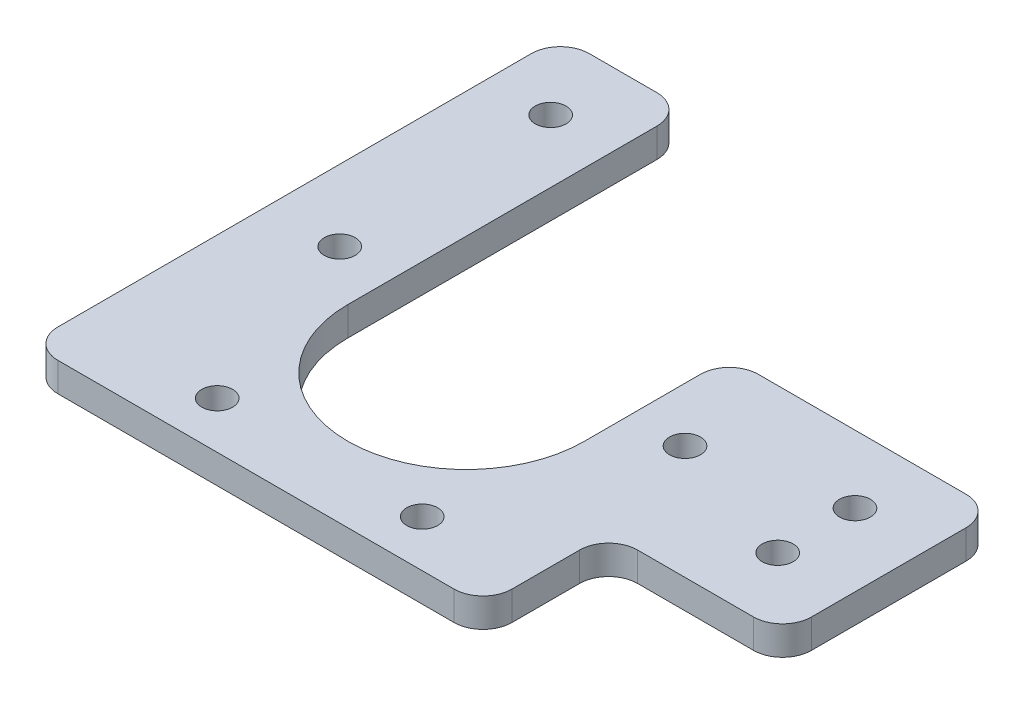
SolidWorks part; units mm, degrees
material "Thornel Mat VMA"
ref_plane "前视基准面" through (0, 0, 0) normal (0, 0, 1) x (1, 0, 0)
ref_plane "上视基准面" through (0, 0, 0) normal (0, 1, 0) x (1, 0, 0)
ref_plane "右视基准面" through (0, 0, 0) normal (1, 0, 0) x (0, 0, -1)
other "Configuration Table"
sketch "草图1" plane through (0, 0, 0) normal (0, 1, 0) x (1, 0, 0)
  line L0 (-20, -57.5) -> (-20, 57.5) construction
  line L1 (-35, -72.5) -> (35, -72.5) construction
  line L2 (-35, -72.5) -> (-35, 72.5) construction
  line L3 (-35, 72.5) -> (35, 72.5) construction
  line L4 (35, -72.5) -> (35, 72.5) construction
  line L5 (-35, -72.5) -> (35, 72.5) construction
  line L6 (-35, 72.5) -> (35, -72.5) construction
  line L7 (-20, 57.5) -> (20, 57.5) construction
  line L8 (20, -57.5) -> (20, 57.5) construction
  line L9 (-20, -57.5) -> (20, -57.5) construction
  line L10 (-7, 72.5) -> (-7, 57.5) construction
  line L11 (-17, 57.5) -> (-17, 72.5)
  line L12 (-17, 57.5) -> (-17, 37.5)
  line L13 (-17, 72.5) -> (-35, 72.5) construction
  line L14 (-35, 72.5) -> (-35, 17.5) construction
  line L15 (-35, 17.5) -> (35, 17.5) construction
  line L16 (35, 17.5) -> (35, 52.5) construction
  line L17 (35, 52.5) -> (7.5, 52.5)
  line L18 (7.5, 52.5) -> (7.5, 37.5)
  line L19 (-17, 72.5) -> (-30, 72.5)
  line L20 (-30, 72.5) -> (-30, 17.5)
  line L21 (-30, 17.5) -> (35, 17.5) construction
  line L22 (27.5, 65.3148) -> (27.5, 7.0983) construction
  line L23 (-42.8388, 65) -> (9.6264, 65) construction
  line L24 (-4.75, 45.3747) -> (-4.75, 29.3576) construction
  line L25 (-4.75, 37.5) -> (-15.3612, 22.3457) construction
  line L26 (-4.75, 37.5) -> (-22.6196, 42.2882) construction
  line L27 (-30, 17.5) -> (17, 17.5)
  line L28 (17, 17.5) -> (17, 30.5)
  line L29 (17, 30.5) -> (35, 30.5)
  line L30 (35, 30.5) -> (35, 52.5)
  circle A0 centre (-4.75, 37.5) radius 12.25 construction
  arc A1 (-17, 37.5) -> (7.5, 37.5) centre (-4.75, 37.5) ccw
  circle A2 centre (-23.5, 65) radius 1.6
  circle A3 centre (27.5, 45.5) radius 1.6
  circle A4 centre (27.5, 37.5) radius 1.6
  circle A7 centre (-22.6196, 42.2882) radius 1.6
  circle A8 centre (-15.3612, 22.3457) radius 1.6
  circle A9 centre (-4.75, 37.5) radius 18.5 construction
  circle A11 centre (5.8612, 22.3457) radius 1.6
  circle A12 centre (13.1196, 42.2882) radius 1.6
  point P0 (0, 0)
  dimension "D4" = 24.5
  dimension "D13" = 3.2
  dimension "D15" = 7
  dimension "D16" = 7
  dimension "D17" = 37
  dimension "D18" = 35
  dimension "D19" = 70
  dimension "D20" = 3
  dimension "D2" = 42
  dimension "D3" = 70
  dimension "D5" = 10
  dimension "D6" = 20
  dimension "D7" = 20
  dimension "D8" = 13
  dimension "D9" = 145
  dimension "D10" = 5
  dimension "D11" = 7.5
  dimension "D12" = 7.5
  dimension "D14" = 6.5
  dimension "D21" = 22
  dimension "D1" = 15
extrude "凸台-拉伸1" add sketch "草图1" along normal blind 3
fillet "圆角1" radius 3 8 edges at (7.5, 1.5, -52.5) (-17, 1.5, -72.5) (-30, 1.5, -72.5) (-30, 1.5, -17.5) (17, 1.5, -17.5) (17, 1.5, -30.5) (35, 1.5, -30.5) (35, 1.5, -52.5)
